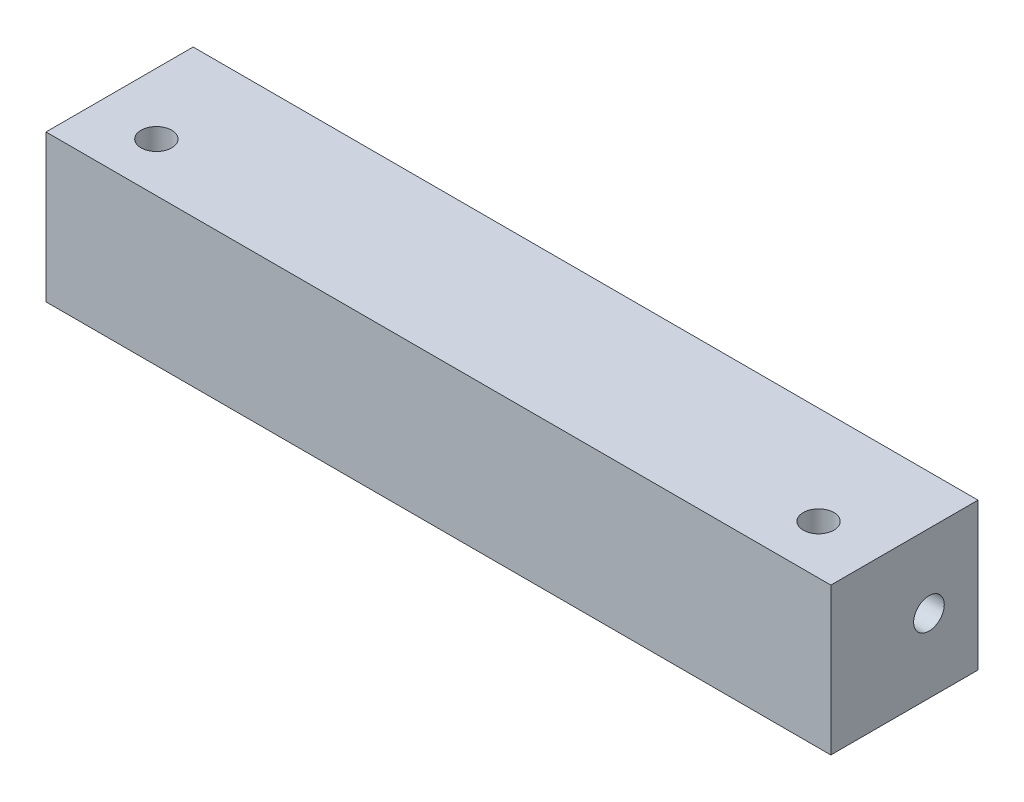
SolidWorks part; units mm, degrees
ref_plane "Plan de face" through (0, 0, 0) normal (0, 0, 1) x (1, 0, 0)
ref_plane "Plan de dessus" through (0, 0, 0) normal (0, 1, 0) x (1, 0, 0)
ref_plane "Plan de droite" through (0, 0, 0) normal (1, 0, 0) x (0, 0, -1)
sketch "Esquisse1" plane through (0, 0, 0) normal (0, 0, 1) x (1, 0, 0)
  line L1 (32, 0) -> (0, 0)
  line L2 (32, 0) -> (32, 6)
  line L3 (32, 6) -> (0, 6)
  line L4 (0, 0) -> (0, 6)
  point P4 (0, 0)
  dimension "D1" = 32
  dimension "D2" = 6
extrude "Boss.-Extru.1" add sketch "Esquisse1" along normal blind 6
sketch "Esquisse2" plane through (32, 0, 0) normal (1, 0, 0) x (0, 0, -1)
  circle A0 centre (-2, 3) radius 0.625
  dimension "D3" = 1.25
  dimension "D1" = 2
  dimension "D2" = 3
extrude "Enlèv. mat.-Extru.1" cut sketch "Esquisse2" against normal through all
sketch "Esquisse3" plane through (0, 6, 0) normal (0, 1, 0) x (1, 0, 0)
  line L0 (0, -6) -> (0, 0) construction
  line L1 (32, -6) -> (32, 0) construction
  circle A0 centre (29.5, -4) radius 0.625
  circle A1 centre (2.5, -4) radius 0.625
  dimension "D1" = 1.25
  dimension "D2" = 1.25
  dimension "D3" = 2.5
  dimension "D4" = 2.5
  dimension "D5" = 2
  dimension "D6" = 2
extrude "Enlèv. mat.-Extru.2" cut sketch "Esquisse3" against normal through all
